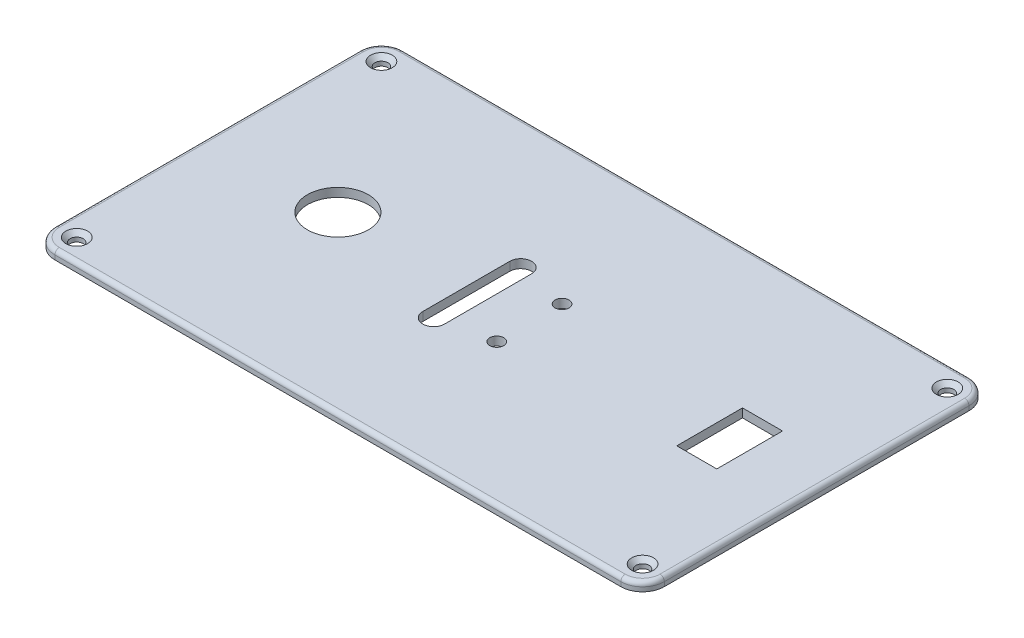
SolidWorks part; units mm, degrees
ref_plane "Alzado" through (0, 0, 0) normal (0, 0, 1) x (1, 0, 0)
ref_plane "Planta" through (0, 0, 0) normal (0, 1, 0) x (1, 0, 0)
ref_plane "Vista lateral" through (0, 0, 0) normal (1, 0, 0) x (0, 0, -1)
sketch "Croquis1" plane through (0, 0, 0) normal (0, 1, 0) x (1, 0, 0)
  line L1 (-65, -40) -> (65, -40)
  line L2 (-70, -35) -> (-70, 35)
  line L3 (-65, 40) -> (65, 40)
  line L4 (70, -35) -> (70, 35)
  line L5 (-70, -40) -> (70, 40) construction
  line L6 (-70, 40) -> (70, -40) construction
  arc A0 (-65, -40) -> (-70, -35) centre (-65, -35) cw
  arc A1 (65, -40) -> (70, -35) centre (65, -35) ccw
  arc A2 (65, 40) -> (70, 35) centre (65, 35) cw
  arc A3 (-70, 35) -> (-65, 40) centre (-65, 35) cw
  point P0 (0, 0)
  dimension "D3" = 5
  dimension "D1" = 140
  dimension "D2" = 80
extrude "Saliente-Extruir1" add sketch "Croquis1" along normal blind 2
sketch "Croquis2" plane through (0, 2, 0) normal (0, 1, 0) x (1, 0, 0)
  line L0 (-1.1, 0) -> (1.1, 0) construction
  line L1 (0, -1.1) -> (0, 1.1) construction
  circle A0 centre (65, 35) radius 1.5
  circle A1 centre (65, -35) radius 1.5
  circle A2 centre (-65, -35) radius 1.5
  circle A3 centre (-65, 35) radius 1.5
  dimension "D1" = 3
extrude "Cortar-Extruir1" cut sketch "Croquis2" against normal blind 2
chamfer "Chaflán1" distance 1 angle 45 4 edges at (65, 2, -33.5) (65, 2, 33.5) (-65, 2, 36.5) (-65, 2, -36.5)
sketch "Croquis3" plane through (0, 2, 0) normal (0, 1, 0) x (1, 0, 0)
  line L0 (0, 0) -> (4, 0) construction
  line L1 (4, -7.5) -> (4, 7.5) construction
  line L2 (0, 0) -> (-8, 0) construction
  line L3 (-8, -10) -> (-8, 10) construction
  line L4 (-10.5, -10) -> (-10.5, 10) construction
  line L5 (-5.5, -10) -> (-5.5, 10) construction
  line L6 (-8, -10) -> (-8, 10) construction
  line L7 (-10.5, -10) -> (-10.5, 10)
  line L8 (-5.5, -10) -> (-5.5, 10)
  circle A0 centre (4, 7.5) radius 1.6
  circle A1 centre (4, -7.5) radius 1.6
  arc A2 (-10.5, -10) -> (-5.5, -10) centre (-8, -10) ccw construction
  arc A3 (-5.5, 10) -> (-10.5, 10) centre (-8, 10) ccw construction
  arc A4 (-10.5, -10) -> (-5.5, -10) centre (-8, -10) ccw
  arc A5 (-5.5, 10) -> (-10.5, 10) centre (-8, 10) ccw
  point P6 (4, 0)
  point P11 (-8, 0)
  point P18 (-8, 0)
  dimension "D2" = 3.2
  dimension "D3" = 3.2
  dimension "D1" = 15
  dimension "D4" = 4
  dimension "D5" = 8
extrude "Cortar-Extruir2" cut sketch "Croquis3" against normal blind 2
sketch "Croquis4" plane through (0, 2, 0) normal (0, 1, 0) x (1, 0, 0)
  line L0 (0, 0) -> (50, 0) construction
  line L1 (0, 0) -> (-40, 0) construction
  line L2 (45.4, 7.55) -> (54.6, 7.55)
  line L3 (45.4, 7.55) -> (45.4, -7.55)
  line L4 (45.4, -7.55) -> (54.6, -7.55)
  line L5 (54.6, 7.55) -> (54.6, -7.55)
  line L6 (45.4, 7.55) -> (54.6, -7.55) construction
  line L7 (45.4, -7.55) -> (54.6, 7.55) construction
  circle A0 centre (-40, 0) radius 7
  dimension "D3" = 14
  dimension "D1" = 15.1
  dimension "D2" = 9.2
extrude "Cortar-Extruir3" cut sketch "Croquis4" against normal blind 2
fillet "Redondeo1" radius 1 8 edges at (68.5355, 2, 38.5355) (0, 2, 40) (-68.5355, 2, 38.5355) (-70, 2, 0) (-68.5355, 2, -38.5355) (0, 2, -40) (68.5355, 2, -38.5355) (70, 2, 0)
